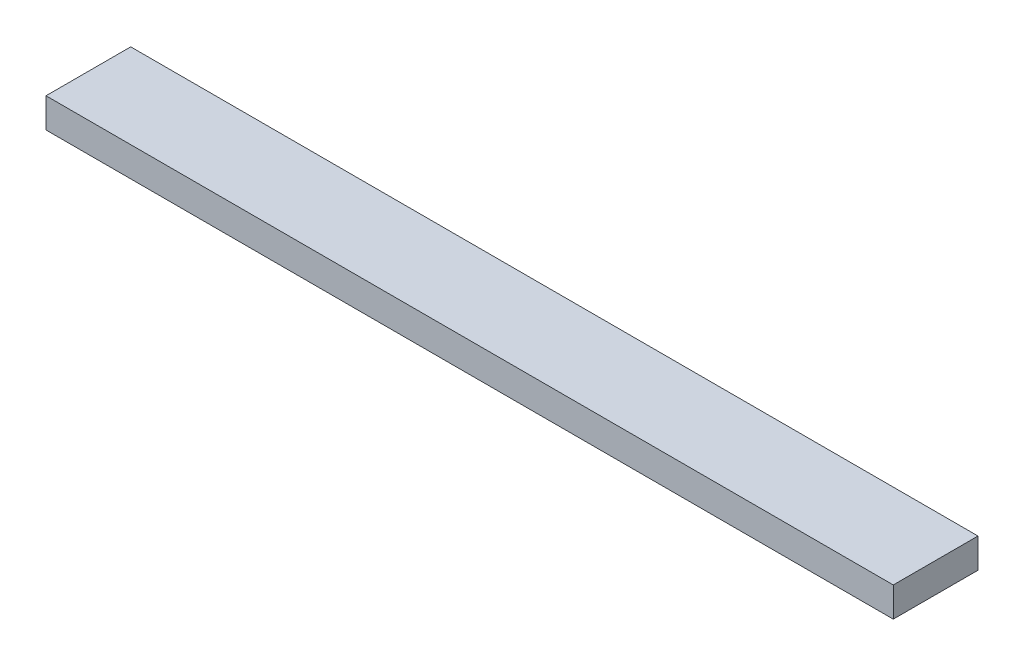
SolidWorks part; units mm, degrees
ref_plane "Front Plane" through (0, 0, 0) normal (0, 0, 1) x (1, 0, 0)
ref_plane "Top Plane" through (0, 0, 0) normal (0, 1, 0) x (1, 0, 0)
ref_plane "Right Plane" through (0, 0, 0) normal (1, 0, 0) x (0, 0, -1)
sketch "Sketch1" plane through (0, 0, 0) normal (0, 1, 0) x (1, 0, 0)
  line L1 (-10, -1) -> (10, -1)
  line L2 (-10, -1) -> (-10, 1)
  line L3 (-10, 1) -> (10, 1)
  line L4 (10, -1) -> (10, 1)
  line L5 (-10, -1) -> (10, 1) construction
  line L6 (-10, 1) -> (10, -1) construction
  point P0 (0, 0)
  dimension "D1" = 2
  dimension "D2" = 20
extrude "Boss-Extrude1" add sketch "Sketch1" along normal blind 0.7
